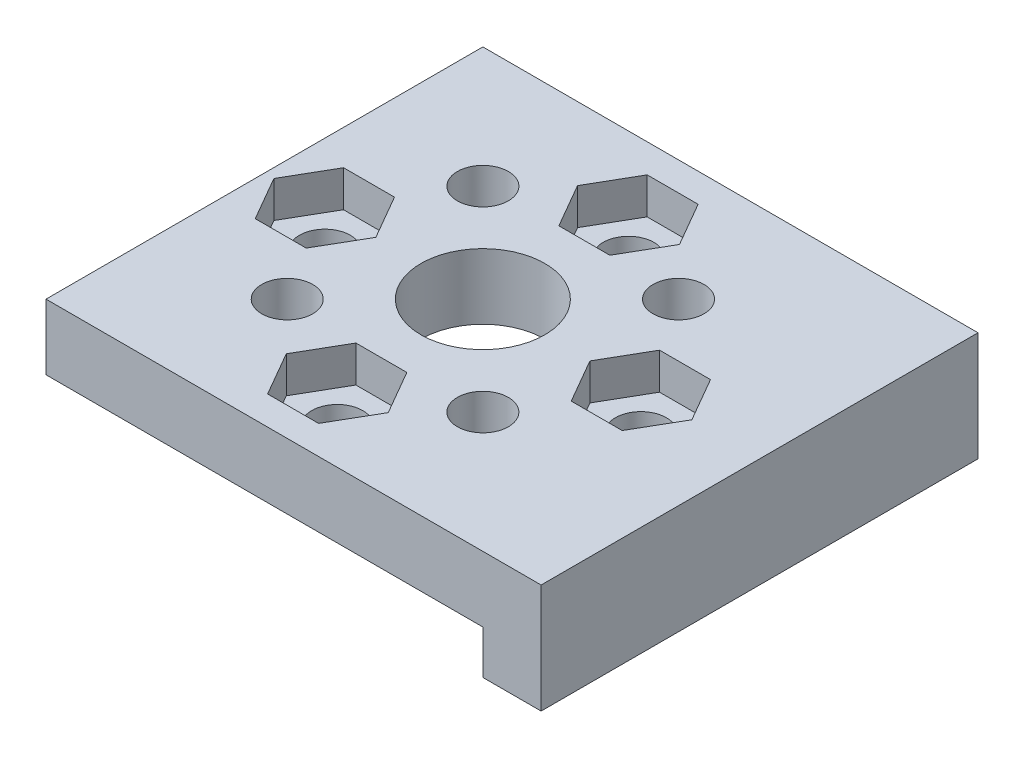
SolidWorks part; units mm, degrees
material "Zero density"
ref_plane "Piano frontale" through (0, 0, 0) normal (0, 0, 1) x (1, 0, 0)
ref_plane "Piano superiore" through (0, 0, 0) normal (0, 1, 0) x (1, 0, 0)
ref_plane "Piano destro" through (0, 0, 0) normal (1, 0, 0) x (0, 0, -1)
sketch "Schizzo1" plane through (0, 0, 0) normal (0, 1, 0) x (1, 0, 0)
  line L12 (-15, 0) -> (15, 0) construction
  line L13 (15, -15) -> (-15, -15)
  line L14 (15, -15) -> (15, 15)
  line L15 (15, 15) -> (-15, 15)
  line L16 (-15, -15) -> (-15, 15)
  line L17 (15, -15) -> (-15, 15) construction
  line L18 (15, 15) -> (-15, -15) construction
  line L19 (0, 15) -> (0, -15) construction
  line L20 (-6.7175, -6.7175) -> (0, 0) construction
  line L21 (0, 0) -> (6.7175, -6.7175) construction
  line L22 (-6.7175, 6.7175) -> (0, 0) construction
  line L23 (0, 0) -> (6.7175, 6.7175) construction
  line L25 (12.6, -3.0311) -> (14.35, 0)
  line L26 (14.35, 0) -> (12.6, 3.0311)
  line L27 (12.6, 3.0311) -> (9.1, 3.0311)
  line L28 (9.1, 3.0311) -> (7.35, 0)
  line L29 (7.35, 0) -> (9.1, -3.0311)
  line L30 (9.1, -3.0311) -> (12.6, -3.0311)
  line L31 (-3.5, -10) -> (-1.75, -13.0311)
  line L32 (-1.75, -13.0311) -> (1.75, -13.0311)
  line L33 (1.75, -13.0311) -> (3.5, -10)
  line L34 (3.5, -10) -> (1.75, -6.9689)
  line L35 (1.75, -6.9689) -> (-1.75, -6.9689)
  line L36 (-1.75, -6.9689) -> (-3.5, -10)
  line L37 (-14.35, 0) -> (-12.6, -3.0311)
  line L38 (-12.6, -3.0311) -> (-9.1, -3.0311)
  line L39 (-9.1, -3.0311) -> (-7.35, 0)
  line L40 (-7.35, 0) -> (-9.1, 3.0311)
  line L41 (-9.1, 3.0311) -> (-12.6, 3.0311)
  line L42 (-12.6, 3.0311) -> (-14.35, 0)
  line L43 (1.75, 6.9689) -> (3.5, 10)
  line L44 (3.5, 10) -> (1.75, 13.0311)
  line L45 (1.75, 13.0311) -> (-1.75, 13.0311)
  line L46 (-1.75, 13.0311) -> (-3.5, 10)
  line L47 (-3.5, 10) -> (-1.75, 6.9689)
  line L48 (-1.75, 6.9689) -> (1.75, 6.9689)
  circle A0 centre (0, 0) radius 9.5 construction
  circle A1 centre (6.7175, -6.7175) radius 1.75
  circle A2 centre (-6.7175, -6.7175) radius 1.75
  circle A3 centre (-6.7175, 6.7175) radius 1.75
  circle A4 centre (6.7175, 6.7175) radius 1.75
  circle A5 centre (0, 0) radius 4.25
  circle A10 centre (0, -10) radius 1.75 construction
  circle A11 centre (0, 10) radius 1.75 construction
  circle A12 centre (-10.85, 0) radius 1.75 construction
  circle A13 centre (10.85, 0) radius 1.75 construction
  circle A14 centre (10.85, 0) radius 3.0311 construction
  circle A15 centre (0, -10) radius 3.0311 construction
  circle A16 centre (-10.85, 0) radius 3.0311 construction
  circle A17 centre (0, 10) radius 3.0311 construction
  point P25 (0, 0)
  dimension "D2" = 19
  dimension "D3" = 3.5
  dimension "D5" = 8.5
  dimension "D4" = 90
  dimension "D9" = 3.5
  dimension "D1" = 30
  dimension "D6" = 90
  dimension "D7" = 90
  dimension "D8" = 30
  dimension "D10" = 5
  dimension "D11" = 4.15
  dimension "D12" = 3.5
extrude "PiastraAggancio" add sketch "Schizzo1" along normal blind 4.5
sketch "Schizzo4" plane through (15, 0, 0) normal (1, 0, 0) x (0, 0, -1)
  line L0 (-15, 4.5) -> (15, 4.5) construction
  line L1 (-29, 4.5) -> (29, 4.5)
  line L2 (-29, 4.5) -> (-29, -34.5)
  line L3 (-29, -34.5) -> (29, -34.5)
  line L4 (29, 4.5) -> (29, -34.5)
  point P6 (0, 4.5)
  point P7 (0, 4.5)
  dimension "D1" = 39
  dimension "D2" = 58
extrude "BaseESC" add sketch "Schizzo4" along normal blind 4
sketch "Schizzo5" plane through (19, 0, 0) normal (1, 0, 0) x (0, 0, -1)
  line L1 (-25, 1.5) -> (-17, 1.5)
  line L2 (-25, 1.5) -> (-25, -2.5)
  line L3 (-25, -2.5) -> (-17, -2.5)
  line L4 (-17, 1.5) -> (-17, -2.5)
  line L5 (-29, -15) -> (0, -15) construction
  line L6 (-29, 4.5) -> (-29, -34.5) construction
  line L7 (0, -15) -> (0, 4.5) construction
  line L8 (29, 4.5) -> (-29, 4.5) construction
  line L9 (25, -2.5) -> (17, -2.5)
  line L10 (17, 1.5) -> (17, -2.5)
  line L11 (25, 1.5) -> (17, 1.5)
  line L12 (25, 1.5) -> (25, -2.5)
  line L13 (25, -31.5) -> (25, -27.5)
  line L14 (25, -31.5) -> (17, -31.5)
  line L15 (17, -31.5) -> (17, -27.5)
  line L16 (25, -27.5) -> (17, -27.5)
  line L17 (-25, -27.5) -> (-17, -27.5)
  line L18 (-17, -31.5) -> (-17, -27.5)
  line L19 (-25, -31.5) -> (-17, -31.5)
  line L20 (-25, -31.5) -> (-25, -27.5)
  dimension "D1" = 4
  dimension "D2" = 3
  dimension "D3" = 2
  dimension "D4" = 8
extrude "AperturaFascetta" cut sketch "Schizzo5" against normal through all
ref_plane "PianoViti" through (0, 0, 6.7175) normal (0, 0, 1) x (1, 0, 0)
sketch "Schizzo7" plane through (0, 0, 6.7175) normal (0, 0, 1) x (1, 0, 0)
  line L0 (-9.2175, 0) -> (-8.4675, 2)
  line L1 (15, 0) -> (-15, 0) construction
  line L2 (-8.4675, 4.5) -> (-8.4675, 0) construction
  line L3 (-8.4675, 2) -> (-6.7175, 2)
  line L4 (-6.7175, 2) -> (-6.7175, 0)
  line L5 (-8.4675, 0) -> (-4.9675, 0) construction
  line L6 (-6.7175, 0) -> (-9.2175, 0)
  dimension "D1" = 2
  dimension "D2" = 2.5
revolve "SvasaturaVitiInferiori" cut sketch "Schizzo7" angle 360 about L4
mirror "SvasaturaVitiInferiori2" about plane through (0, 0, 0) normal (1, 0, 0) of "SvasaturaVitiInferiori"
ref_plane "PianoMedio" through (0, 0, 0) normal (0, 0, 1) x (1, 0, 0)
mirror "SvasaturaVitiInferiori3" about plane through (0, 0, 0) normal (0, 0, 1) of "SvasaturaVitiInferiori2", "SvasaturaVitiInferiori"
sketch "Schizzo8" plane through (0, 0, 0) normal (0, -1, 0) x (1, 0, 0)
  line L0 (1.75, -13.0311) -> (-1.75, -13.0311) construction
  line L1 (1.75, -13.0311) -> (3.5, -10)
  line L2 (3.5, -10) -> (1.75, -6.9689)
  line L3 (1.75, -6.9689) -> (-1.75, -6.9689)
  line L4 (-1.75, -6.9689) -> (-3.5, -10)
  line L5 (-3.5, -10) -> (-1.75, -13.0311)
  line L6 (-1.75, -13.0311) -> (1.75, -13.0311)
  line L7 (18.7, 0) -> (-18.7, 0) construction
  line L8 (12.6, 3.0311) -> (9.1, 3.0311)
  line L9 (9.1, 3.0311) -> (7.35, 0)
  line L10 (7.35, 0) -> (9.1, -3.0311)
  line L11 (9.1, -3.0311) -> (12.6, -3.0311)
  line L12 (12.6, -3.0311) -> (14.35, 0)
  line L13 (14.35, 0) -> (12.6, 3.0311)
  line L15 (-1.75, 13.0311) -> (-3.5, 10)
  line L16 (-3.5, 10) -> (-1.75, 6.9689)
  line L17 (-1.75, 6.9689) -> (1.75, 6.9689)
  line L18 (1.75, 6.9689) -> (3.5, 10)
  line L19 (3.5, 10) -> (1.75, 13.0311)
  line L20 (1.75, 13.0311) -> (-1.75, 13.0311)
  line L21 (-14.35, 0) -> (-12.6, -3.0311)
  line L22 (-12.6, -3.0311) -> (-9.1, -3.0311)
  line L23 (-9.1, -3.0311) -> (-7.35, 0)
  line L24 (-7.35, 0) -> (-9.1, 3.0311)
  line L25 (-9.1, 3.0311) -> (-12.6, 3.0311)
  line L26 (-12.6, 3.0311) -> (-14.35, 0)
  circle A0 centre (0, -10) radius 3.0311 construction
  circle A1 centre (0, -10) radius 1.75
  circle A2 centre (10.85, 0) radius 3.0311 construction
  circle A3 centre (0, 10) radius 3.0311 construction
  circle A4 centre (-10.85, 0) radius 3.0311 construction
  circle A5 centre (10.85, 0) radius 1.75
  circle A6 centre (0, 10) radius 1.75
  circle A7 centre (-10.85, 0) radius 1.75
  dimension "D1" = 3.5
extrude "ChiusuraForiEsagonali" add sketch "Schizzo8" against normal blind 2
sketch "Schizzo9" plane through (15, 0, 0) normal (-1, 0, 0) x (0, 0, 1)
  line L0 (-15, 0) -> (-15, -3)
  line L1 (-15, -3) -> (15, -3)
  line L2 (15, -3) -> (15, 0)
  line L8 (-15, 0) -> (-15, 4.5)
  line L9 (-15, 4.5) -> (-29, 4.5)
  line L10 (-29, 4.5) -> (-29, -34.5)
  line L11 (-29, -34.5) -> (29, -34.5)
  line L12 (29, -34.5) -> (29, 4.5)
  line L13 (29, 4.5) -> (15, 4.5)
  line L14 (15, 4.5) -> (15, 0)
  line L15 (15, 0) -> (-15, 0)
  line L16 (-15, 0) -> (-15, 4.5)
  line L17 (-15, 4.5) -> (-29, 4.5)
  line L18 (-29, 4.5) -> (-29, -34.5)
  line L19 (-29, -34.5) -> (29, -34.5)
  line L20 (29, -34.5) -> (29, 4.5)
  line L21 (29, 4.5) -> (15, 4.5)
  line L22 (15, 4.5) -> (15, 0)
  dimension "D2" = 3
  dimension "D1" = 0
extrude "RimozionePiastaESC" cut sketch "Schizzo9" against normal blind 10
